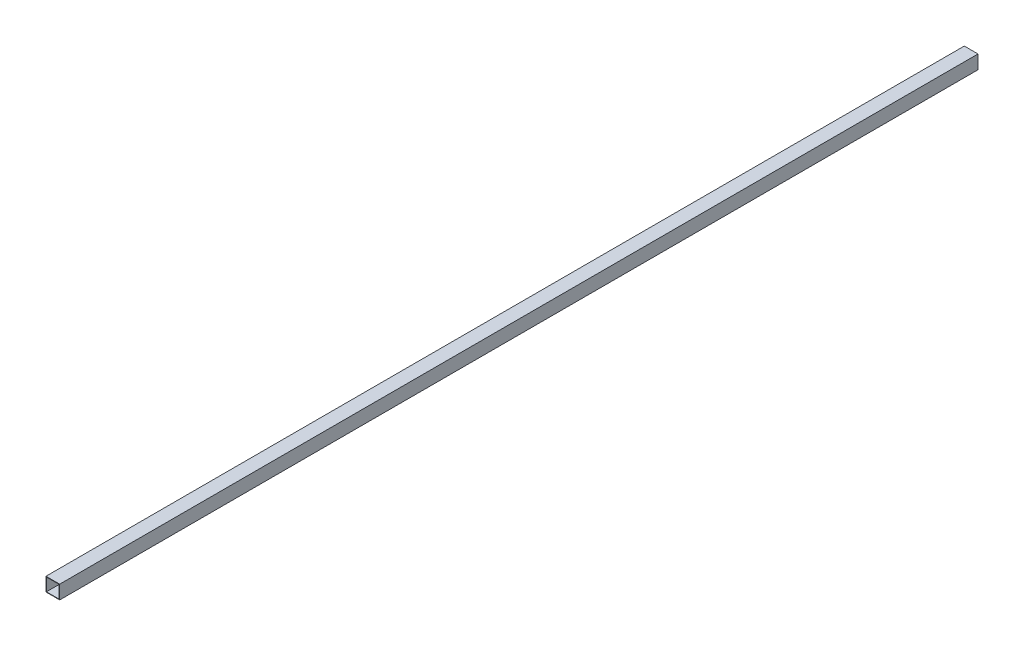
SolidWorks part; units mm, degrees
ref_plane "Alzado" through (0, 0, 0) normal (0, 0, 1) x (1, 0, 0)
ref_plane "Planta" through (0, 0, 0) normal (0, 1, 0) x (1, 0, 0)
ref_plane "Vista lateral" through (0, 0, 0) normal (1, 0, 0) x (0, 0, -1)
sketch "Croquis1" plane through (0, 0, 0) normal (0, 0, 1) x (1, 0, 0)
  line L1 (15, -15) -> (-15, -15)
  line L2 (15, -15) -> (15, 15)
  line L3 (15, 15) -> (-15, 15)
  line L4 (-15, -15) -> (-15, 15)
  line L5 (15, -15) -> (-15, 15) construction
  line L6 (15, 15) -> (-15, -15) construction
  circle A0 centre (0, 0) radius 21.2132 construction
  point P0 (0, 0)
  dimension "D1" = 30
extrude "Extruir-Lámina1" add sketch "Croquis1" along normal mid plane 2010 thin
